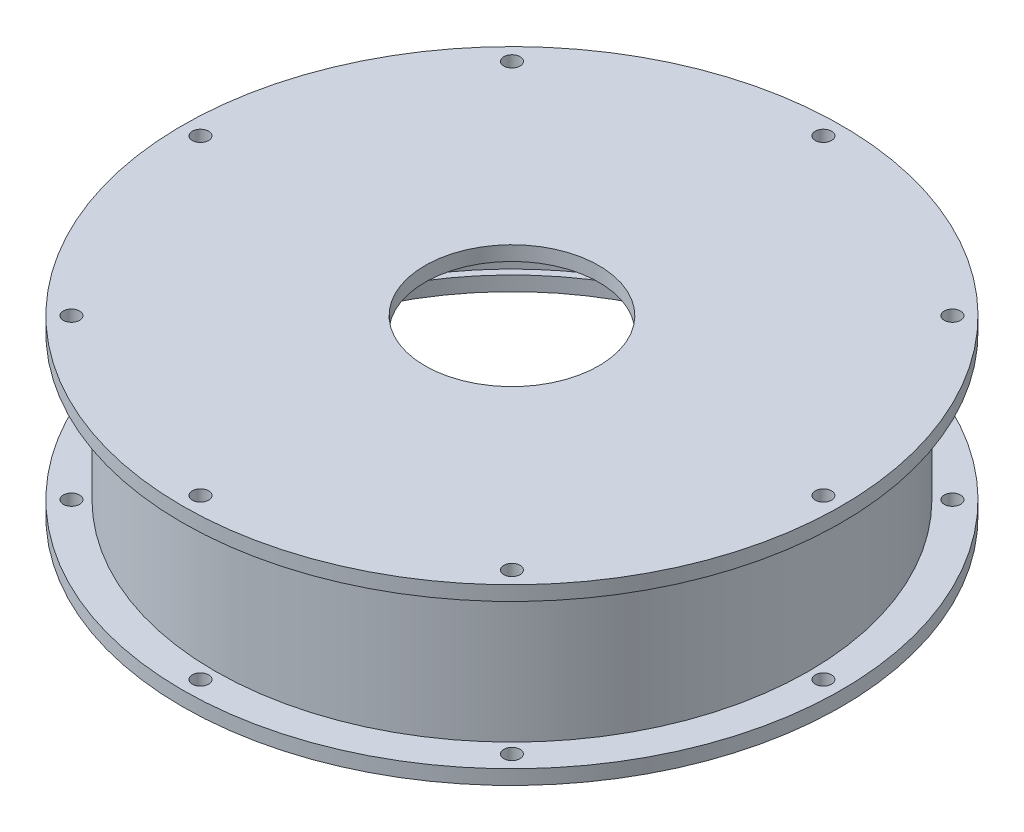
SolidWorks part; units mm, degrees
material "6061-T6 (SS)"
ref_plane "Front Plane" through (0, 0, 0) normal (0, 0, 1) x (1, 0, 0)
ref_plane "Top Plane" through (0, 0, 0) normal (0, 1, 0) x (1, 0, 0)
ref_plane "Right Plane" through (0, 0, 0) normal (1, 0, 0) x (0, 0, -1)
sketch "Sketch1" plane through (0, 0, 0) normal (0, 1, 0) x (1, 0, 0)
  circle A0 centre (0, 0) radius 144.4625
  dimension "D1" = 288.925
extrude "Boss-Extrude1" add sketch "Sketch1" along normal blind 6.35 contours A0
sketch "Sketch2" plane through (0, 6.35, 0) normal (0, 1, 0) x (1, 0, 0)
  circle A0 centre (0, 0) radius 136.525
  point P3 (0, 136.525)
  point P4 (96.5378, 96.5378)
  point P5 (136.525, 0)
  point P8 (96.5378, -96.5378)
  point P9 (0, -136.525)
  point P10 (-96.5378, -96.5378)
  point P11 (-136.525, 0)
  point P12 (-96.5378, 96.5378)
  dimension "D1" = 273.05
  dimension "D2" = 8
hole_wizard "1/4 Clearance Hole1" positions "Sketch2" profile "Sketch3" hole size "1/4" standard "ANSI Inch" end condition up to next
sketch "Sketch3" plane through (-96.5378, 6.35, -96.5378) normal (1, 0, 0) x (0, 0, 1)
  line L0 (0, 0) -> (0, 6.35)
  line L1 (0, 6.35) -> (3.5712, 6.35)
  line L2 (3.5712, 6.35) -> (3.5712, 0)
  line L5 (3.5712, 0) -> (0, 0)
  line L11 (0, -6.35) -> (0, 107.95) construction
  dimension "Thru Hole Dia." = 7.1425
  dimension "Thru Hole Depth" = 6.35
sketch "Sketch4" plane through (0, 6.35, 0) normal (0, 1, 0) x (1, 0, 0)
  circle A0 centre (0, 0) radius 130.175
  circle A1 centre (0, 0) radius 123.825
  dimension "D1" = 260.35
  dimension "D2" = 247.65
extrude "Boss-Extrude2" add sketch "Sketch4" along normal blind 63.5
ref_plane "Plane1" through (0, 72.39, 0) normal (0, 1, 0) x (1, 0, 0)
ref_plane "Plane3" through (0, 38.1, 0) normal (0, 1, 0) x (1, 0, 0)
mirror "Mirror2" about plane through (0, 38.1, 0) normal (0, 1, 0) of "Boss-Extrude1"
mirror "Mirror3" about plane through (0, 38.1, 0) normal (0, 1, 0) of "1/4 Clearance Hole1"
sketch "Sketch7" plane through (0, 0, 0) normal (0, -1, 0) x (1, 0, 0)
  circle A0 centre (0, 0) radius 120.65
  dimension "D1" = 241.3
extrude "Cut-Extrude1" cut sketch "Sketch7" against normal blind 69.85
sketch "Sketch8" plane through (0, 76.2, 0) normal (0, 1, 0) x (1, 0, 0)
  circle A0 centre (0, 0) radius 38.1
  dimension "D1" = 76.2
extrude "Cut-Extrude2" cut sketch "Sketch8" against normal up to next
